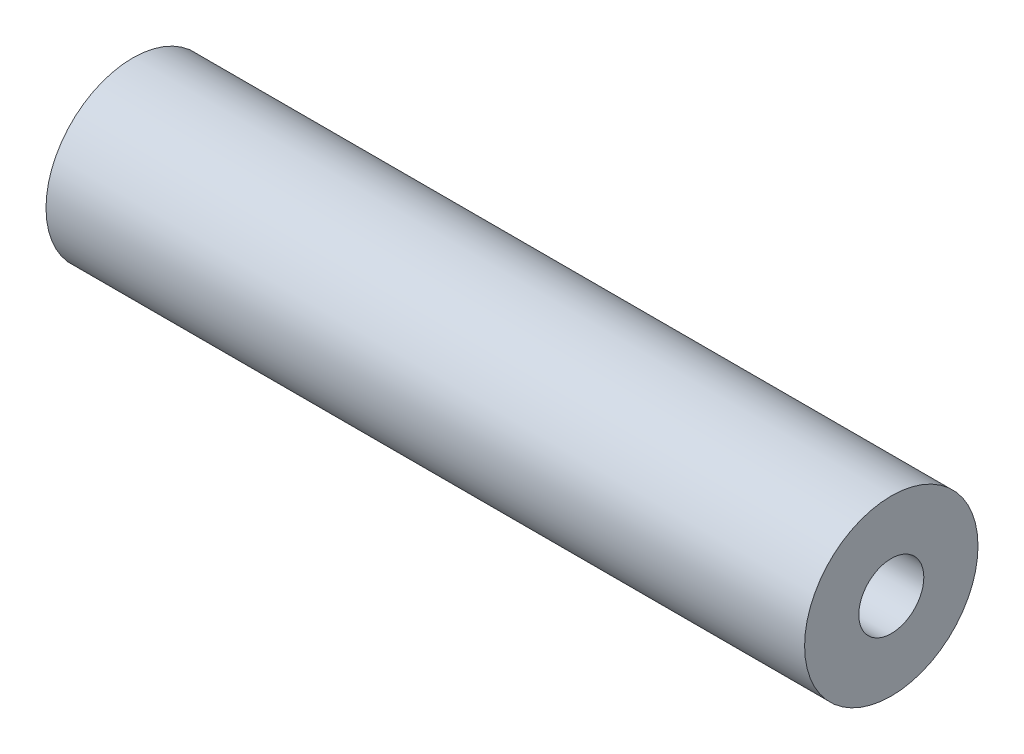
SolidWorks part; units mm, degrees
material "1060 合金"
ref_plane "正面" through (0, 0, 0) normal (0, 0, 1) x (1, 0, 0)
ref_plane "平面" through (0, 0, 0) normal (0, 1, 0) x (1, 0, 0)
ref_plane "右側面" through (0, 0, 0) normal (1, 0, 0) x (0, 0, -1)
sketch "ｽｹｯﾁ1" plane through (0, 0, 0) normal (1, 0, 0) x (0, 0, -1)
  circle A0 centre (0, 0) radius 4
  circle A1 centre (0, 0) radius 1.5
  dimension "D1" = 8
  dimension "D2" = 3
extrude "ﾎﾞｽ - 押し出し1" add sketch "ｽｹｯﾁ1" along normal blind 35
